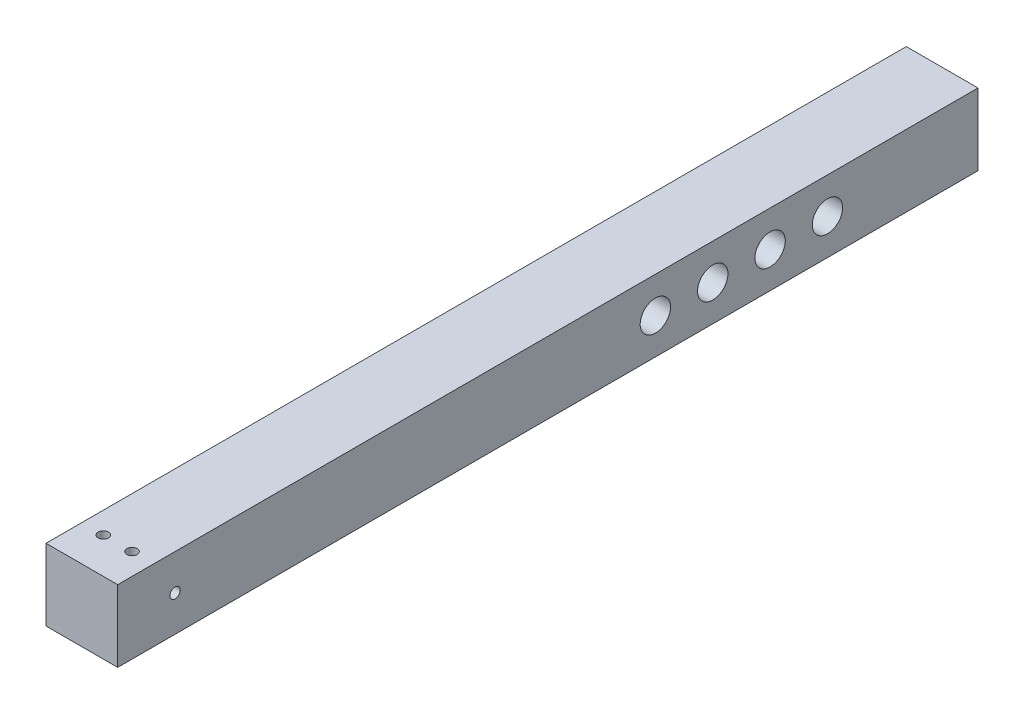
SolidWorks part; units mm, degrees
ref_plane "Front Plane" through (0, 0, 0) normal (0, 0, 1) x (1, 0, 0)
ref_plane "Top Plane" through (0, 0, 0) normal (0, 1, 0) x (1, 0, 0)
ref_plane "Right Plane" through (0, 0, 0) normal (1, 0, 0) x (0, 0, -1)
sketch "Sketch1" plane through (0, 0, 0) normal (0, 0, 1) x (1, 0, 0)
  line L1 (-12.5, 12.5) -> (12.5, 12.5)
  line L2 (-12.5, 12.5) -> (-12.5, -12.5)
  line L3 (-12.5, -12.5) -> (12.5, -12.5)
  line L4 (12.5, 12.5) -> (12.5, -12.5)
  line L5 (-12.5, 12.5) -> (12.5, -12.5) construction
  line L6 (-12.5, -12.5) -> (12.5, 12.5) construction
  point P0 (0, 0)
  dimension "D1" = 25
  dimension "D2" = 25
extrude "Boss-Extrude1" add sketch "Sketch1" along normal blind 200
sketch "Sketch2" plane through (12.5, 0, 0) normal (1, 0, 0) x (0, 0, -1)
  line L0 (-200, -12.5) -> (0, -12.5) construction
  line L1 (0, 12.5) -> (-25, 12.5) construction
  line L2 (0, 12.5) -> (0, -12.5) construction
  line L3 (0, -12.5) -> (-25, -12.5) construction
  line L4 (-25, 12.5) -> (-25, -12.5) construction
  line L5 (0, 12.5) -> (-25, -12.5) construction
  line L6 (0, -12.5) -> (-25, 12.5) construction
  line L7 (0, -12.5) -> (0, 12.5) construction
  circle A0 centre (-12.5, 0) radius 2.5
  point P0 (-12.5, 0)
  dimension "D1" = 25
extrude "Cut-Extrude1" cut sketch "Sketch2" against normal through all
sketch "Sketch3" plane through (0, 12.5, 0) normal (0, 1, 0) x (1, 0, 0)
  line L0 (12.5, -200) -> (-12.5, -200) construction
  line L2 (0, -1000) -> (0, 49000) construction
  circle A0 centre (-5, -187.5) radius 1.8
  circle A1 centre (5, -187.5) radius 1.8
  dimension "D1" = 3.6
  dimension "D2" = 3.6
  dimension "D3" = 12.5
  dimension "D4" = 5
  dimension "D5" = 5
extrude "Cut-Extrude2" cut sketch "Sketch3" against normal through all
sketch "Sketch4" plane through (-12.5, 0, 0) normal (-1, 0, 0) x (0, 0, 1)
  line L0 (200, -12.5) -> (0, -12.5) construction
  line L2 (200, 12.5) -> (200, -12.5) construction
  circle A0 centre (180, 0) radius 1.8
  dimension "D1" = 3.6
  dimension "D3" = 20
  dimension "D2" = 12.5
extrude "Cut-Extrude3" cut sketch "Sketch4" against normal through all both and the other way through all
ref_plane "Plane1" through (0, 0, 12.5) normal (0, 0, -1) x (-1, 0, 0)
mirror "Mirror2" about plane through (0, 0, 12.5) normal (0, 0, -1) of "Cut-Extrude3", "Cut-Extrude2", "Cut-Extrude1", "Boss-Extrude1"
sketch "Sketch6" plane through (12.5, 0, 0) normal (1, 0, 0) x (0, 0, -1)
  line L0 (175, -12.5) -> (175, 12.5) construction
  line L1 (-12.5, -1000) -> (-12.5, 49000) construction
  line L2 (-12.5, 0) -> (7.5, 0) construction
  circle A0 centre (155, 0) radius 1.8 construction
  circle A1 centre (7.5, 0) radius 2.5
  circle A4 centre (-12.5, 0) radius 2.5 construction
  circle A5 centre (-12.5, 0) radius 2.5
  circle A6 centre (27.5, 0) radius 2.5
  circle A7 centre (47.5, 0) radius 2.5
  dimension "D1" = 20
  dimension "D5" = 20
  dimension "D4" = 4
extrude "Cut-Extrude5" cut sketch "Sketch6" against normal through all both and the other way through all
sketch "Sketch7" plane through (-12.5, 0, 0) normal (-1, 0, 0) x (0, 0, 1)
  circle A0 centre (-47.5, 0) radius 5.3
  circle A1 centre (-27.5, 0) radius 5.3
  circle A2 centre (-7.5, 0) radius 5.3
  circle A3 centre (12.5, 0) radius 5.3
  dimension "D1" = 10.6
  dimension "D2" = 4
extrude "Cut-Extrude6" cut sketch "Sketch7" against normal through all both and the other way through all
sketch "Sketch8" plane through (-12.5, 0, 0) normal (-1, 0, 0) x (0, 0, 1)
  line L0 (200, 12.5) -> (-175, 12.5) construction
  line L1 (-175, -12.5) -> (-100, -12.5)
  line L2 (-175, -12.5) -> (-175, 12.5)
  line L3 (-175, 12.5) -> (-100, 12.5)
  line L4 (-100, -12.5) -> (-100, 12.5)
  dimension "D1" = 75
extrude "Cut-Extrude7" cut sketch "Sketch8" against normal through all both and the other way through all
